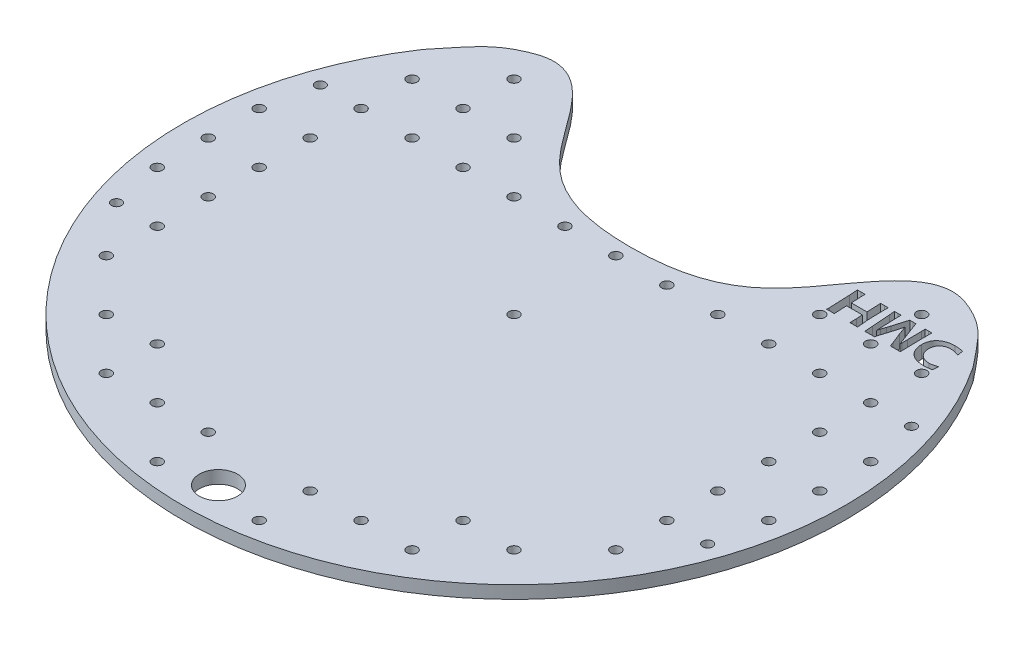
SolidWorks part; units mm, degrees
material "ABS"
ref_plane "Front Plane" through (0, 0, 0) normal (0, 0, 1) x (1, 0, 0)
ref_plane "Top Plane" through (0, 0, 0) normal (0, 1, 0) x (1, 0, 0)
ref_plane "Right Plane" through (0, 0, 0) normal (1, 0, 0) x (0, 0, -1)
sketch "Sketch1" plane through (0, 0, 0) normal (0, 1, 0) x (1, 0, 0)
  circle A0 centre (0, 0) radius 164.975
  dimension "D1" = 329.95
extrude "Boss-Extrude1" add sketch "Sketch1" along normal blind 6.35
ref_point "Point1"
sketch "Sketch2" plane through (0, 0, 0) normal (0, -1, 0) x (1, 0, 0)
  line L0 (0, -1000) -> (0, 49000) construction
  line L1 (-1000, 0) -> (49000, 0) construction
  circle A0 centre (147.32, -50.8) radius 4.7625 construction
  circle A1 centre (147.32, 50.8) radius 4.7625 construction
  circle A2 centre (-147.32, -50.8) radius 4.7625 construction
  circle A3 centre (-147.32, 50.8) radius 4.7625 construction
  point P0 (147.32, -50.8)
  dimension "D1" = 147.32
  dimension "D2" = 50.8
hole_wizard "#10 Clearance Hole1" positions "Sketch4" profile "Sketch3" hole size "#10" standard "Ansi Inch" end condition through all
sketch "Sketch4" plane through (0, 6.35, 0) normal (0, 1, 0) x (-1, 0, 0)
  point P1 (147.32, 50.8)
  point P4 (147.32, -50.8)
  point P7 (-147.32, -50.8)
  point P10 (-147.32, 50.8)
sketch "Sketch3" plane through (-147.32, 6.35, 50.8) normal (1, 0, 0) x (0, 0, 1)
  line L0 (0, 0) -> (0, 6.35)
  line L1 (0, 6.35) -> (2.4892, 6.35)
  line L2 (2.4892, 6.35) -> (2.4892, 0)
  line L5 (2.4892, 0) -> (0, 0)
  line L11 (0, -6.35) -> (0, 107.95) construction
  dimension "Thru Hole Dia." = 4.9784
  dimension "Thru Hole Depth" = 6.35
sketch "Sketch5" plane through (0, 6.35, 0) normal (0, 1, 0) x (1, 0, 0)
  line L0 (0, 201000) -> (0, -249000) construction
  line L1 (-50.8, -55.3589) -> (50.8, -55.3589) construction
  line L2 (-50.8, -55.3589) -> (-50.8, -156.9589) construction
  line L3 (-50.8, -156.9589) -> (50.8, -156.9589) construction
  line L4 (50.8, -55.3589) -> (50.8, -156.9589) construction
  line L5 (-50.8, -55.3589) -> (50.8, -156.9589) construction
  line L6 (-50.8, -156.9589) -> (50.8, -55.3589) construction
  line L7 (0, -106.1589) -> (0, 58.1068) construction
  circle A0 centre (0, 0) radius 164.975 construction
  circle A2 centre (147.32, 50.8) radius 2.4892 construction
  spline S0 degree 3 poles (-137.1735, 91.6525) (-125.7052, 105.9966) (-120.8705, 112.2721) (-90.3531, 124.7653) (-63.3632, 88.0034) (-42.1548, 58.1068) (0, 58.1068) knots 0 0 0 0 0.216331 0.275014 0.586828 1 1 1 1
  spline S1 degree 3 poles (137.1735, 91.6525) (125.7052, 105.9966) (120.8705, 112.2721) (90.3531, 124.7653) (63.3632, 88.0034) (42.1548, 58.1068) (0, 58.1068) knots 0 0 0 0 0.216331 0.275014 0.586828 1 1 1 1
  point P0 (0, -106.1589)
  dimension "D1" = 101.6
  dimension "D2" = 101.6
extrude "Cut-Extrude1" cut sketch "Sketch5" against normal through all and the other way through all contours S0 S1
hole_wizard "#10 Clearance Hole2" positions "Sketch9" profile "Sketch8" hole size "#10" standard "Ansi Inch"
sketch "Sketch9" plane through (0, 0, 0) normal (0, -1, 0) x (1, 0, 0)
  point P1 (0, 0)
sketch "Sketch8" plane through (0, 0, 0) normal (1, 0, 0) x (0, 0, -1)
  line L0 (0, 0) -> (0, 7.8838)
  line L1 (0, 7.8838) -> (2.5527, 6.35)
  line L2 (2.5527, 6.35) -> (2.5527, 0)
  line L5 (2.5527, 0) -> (0, 0)
  line L10 (0, 7.8838) -> (-2.5527, 6.35) construction
  line L11 (0, -6.35) -> (0, 107.95) construction
  dimension "Hole Dia." = 5.1054
  dimension "Hole Depth" = 6.35
  dimension "Drill Angle" = 118
ref_plane "Plane1" through (0, 0, 0) normal (1, 0, 0) x (0, 0, -1)
pattern_linear "LPattern2" count 7 spacing 25.4 along (-1, 0, 0) count 7 spacing 25.4 along (0, 0, 1) skipping (0, 1), (0, 2), (0, 3), (0, 4), (0, 5), (0, 6), (1, 0), (1, 1), (1, 2), (1, 3), (1, 4), (2, 0), (2, 1), (2, 2), (2, 3), (2, 4), (2, 6), (3, 0), (3, 1), (3, 2), (3, 3), (3, 6), (4, 0), (4, 1), (4, 2), (4, 3), (4, 5), (4, 6), (5, 4), (5, 5), (5, 6), (6, 2), (6, 3), (6, 4), (6, 5), (6, 6) of "#10 Clearance Hole2"
pattern_linear "LPattern3" count 5 spacing 25.4 along (0, 0, -1) count 7 spacing 25.4 along (-1, 0, 0) skipping (0, 1), (0, 2), (0, 3), (0, 4), (1, 0), (1, 1), (1, 2), (1, 3), (1, 4), (2, 6), (3, 0), (3, 1), (3, 2), (3, 6), (4, 0), (4, 1), (4, 2), (4, 3), (4, 5), (4, 6) of "#10 Clearance Hole2"
sketch "Sketch10" plane through (0, 0, 0) normal (0, -1, 0) x (1, 0, 0)
  line L0 (0, -58.1068) -> (73.66, -58.1068) construction
  line L1 (73.66, -58.1068) -> (73.66, -96.2068) construction
  line L2 (73.66, -96.2068) -> (124.46, -96.2068) construction
  text T0 "HMC" font "Eras Demi ITC" height 16.002
  dimension "D1" = 73.66
  dimension "D2" = 38.1
  dimension "D3" = 50.8
extrude "Cut-Extrude2" cut sketch "Sketch10" against normal through all
mirror "Mirror1" about plane through (0, 0, 0) normal (1, 0, 0) of "LPattern3", "LPattern2"
sketch "Sketch11" plane through (0, 6.35, 0) normal (0, 1, 0) x (1, 0, 0)
  circle A0 centre (0, -147.32) radius 9.525
  circle A1 centre (0, 0) radius 2.5527 construction
  dimension "D2" = 19.05
  dimension "D1" = 147.32
extrude "Cut-Extrude3" cut sketch "Sketch11" against normal through all
